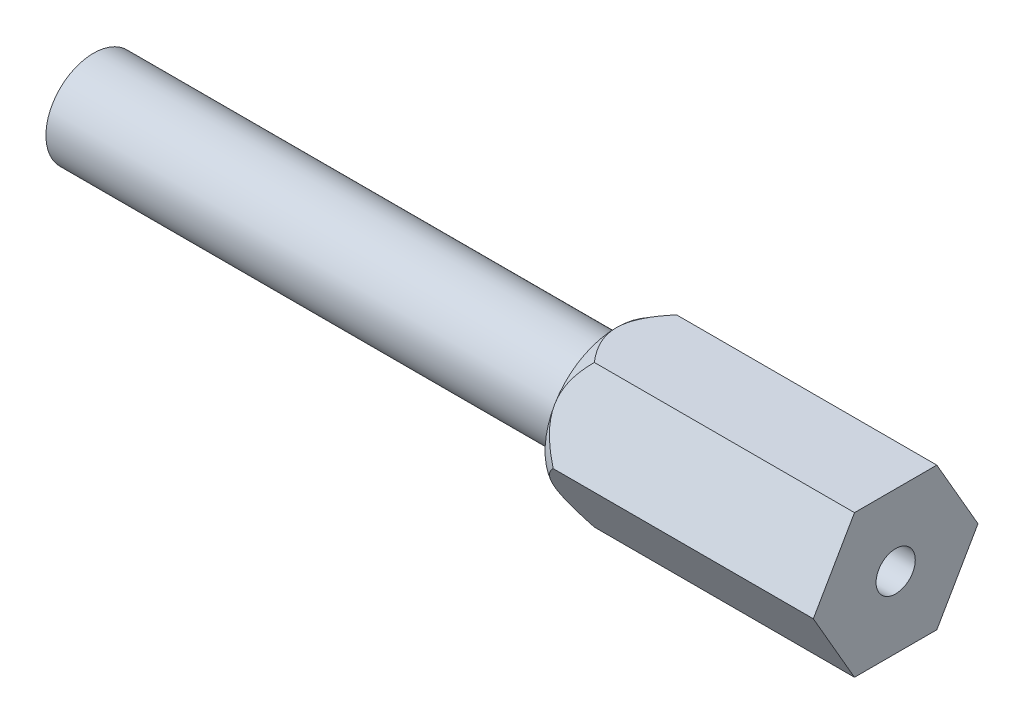
SolidWorks part; units mm, degrees
material "1.0715 (11SMn30)"
ref_plane "Plan de face" through (0, 0, 0) normal (0, 0, 1) x (1, 0, 0)
ref_plane "Plan de dessus" through (0, 0, 0) normal (0, 1, 0) x (1, 0, 0)
ref_plane "Plan de droite" through (0, 0, 0) normal (1, 0, 0) x (0, 0, -1)
sketch "Esquisse1" plane through (0, 0, 0) normal (1, 0, 0) x (0, 0, -1)
  line L1 (6.9282, 0) -> (3.4641, 6)
  line L2 (3.4641, 6) -> (-3.4641, 6)
  line L3 (-3.4641, 6) -> (-6.9282, 0)
  line L4 (-6.9282, 0) -> (-3.4641, -6)
  line L5 (-3.4641, -6) -> (3.4641, -6)
  line L6 (3.4641, -6) -> (6.9282, 0)
  circle A0 centre (0, 0) radius 6 construction
  dimension "D1" = 12
extrude "Boss.-Extru.1" add sketch "Esquisse1" against normal blind 67.5
hole_wizard "Trou taraudé M4x0.71" positions "Esquisse3" profile "Esquisse2" tap size "M4x0.7" standard "Ansi Metric"
sketch "Esquisse3" plane through (0, 0, 0) normal (1, 0, 0) x (0, 0, -1)
  point P0 (0, 0)
sketch "Esquisse2" plane through (0, 0, 0) normal (0, 1, 0) x (0, 0, -1)
  line L0 (0, 0) -> (0, 15.9914)
  line L1 (0, 15.9914) -> (1.65, 15)
  line L2 (1.65, 15) -> (1.65, 0)
  line L5 (1.65, 0) -> (0, 0)
  line L10 (0, 15.9914) -> (-1.65, 15) construction
  line L11 (0, -6.35) -> (0, 107.95) construction
  dimension "Diamètre du trou pour taraudage" = 3.3
  dimension "Profondeur du trou pour taraudage" = 15
  dimension "Angle de pointe" = 118
cosmetic thread "Filetage de perçage1" parameters "D1"=10, "D2"=4
hole_wizard "Trou taraudé M3x0.51" positions "Esquisse6" profile "Esquisse5" tap size "M3x0.5" standard "Ansi Metric"
sketch "Esquisse6" plane through (-67.5, 0, 0) normal (-1, 0, 0) x (0, 0, 1)
  point P0 (0, 0)
sketch "Esquisse5" plane through (-67.5, 0, 0) normal (0, 1, 0) x (0, 0, 1)
  line L0 (0, 0) -> (0, 15.7511)
  line L1 (0, 15.7511) -> (1.25, 15)
  line L2 (1.25, 15) -> (1.25, 0)
  line L5 (1.25, 0) -> (0, 0)
  line L10 (0, 15.7511) -> (-1.25, 15) construction
  line L11 (0, -6.35) -> (0, 107.95) construction
  dimension "Diamètre du trou pour taraudage" = 2.5
  dimension "Profondeur du trou pour taraudage" = 15
  dimension "Angle de pointe" = 118
cosmetic thread "Filetage de perçage2" parameters "D1"=10, "D2"=3
sketch "Esquisse4" plane through (0, 0, 0) normal (0, 1, 0) x (1, 0, 0)
  line L0 (-21.8923, 6.9282) -> (-67.5, 6.9282)
  line L1 (-67.5, 6.9282) -> (0, 6.9282) construction
  line L2 (-67.5, 6.9282) -> (-67.5, 4)
  line L3 (-67.5, 4) -> (-23.5, 4)
  line L4 (-23.5, 4) -> (-23.5, 6)
  line L5 (-23.5, 6) -> (-21.8923, 6.9282)
  line L6 (0, 0) -> (-67.5, 0) construction
  line L7 (-67.5, 3.4641) -> (-67.5, -3.4641) construction
  line L8 (0, 3.4641) -> (0, -3.4641) construction
  dimension "D1" = 8
  dimension "D2" = 12
  dimension "D3" = 30
  dimension "D4" = 23.5
revolve "Enlèvement de matière-Révolution1" cut sketch "Esquisse4" angle 360 about L6
